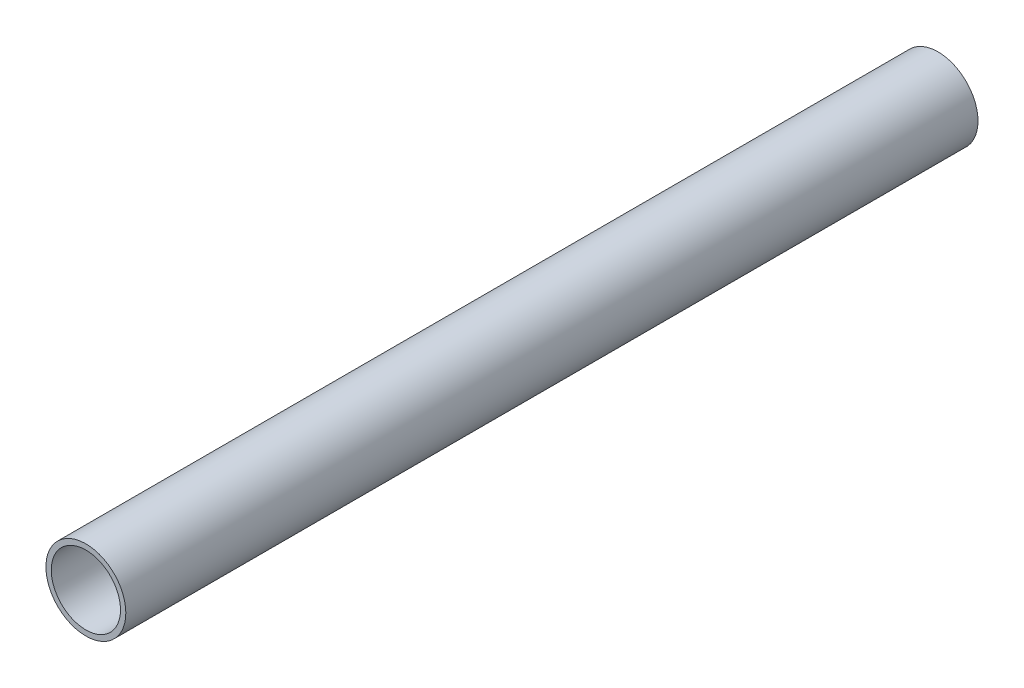
SolidWorks part; units mm, degrees
material "Hexcel AS4C (3000 Filaments)"
ref_plane "Front Plane" through (0, 0, 0) normal (0, 0, 1) x (1, 0, 0)
ref_plane "Top Plane" through (0, 0, 0) normal (0, 1, 0) x (1, 0, 0)
ref_plane "Right Plane" through (0, 0, 0) normal (1, 0, 0) x (0, 0, -1)
sketch "Sketch1" plane through (0, 0, 0) normal (0, 0, 1) x (1, 0, 0)
  circle A0 centre (0, 0) radius 7.5
  circle A1 centre (0, 0) radius 6.5
  dimension "D1" = 15
  dimension "D2" = 13
extrude "Boss-Extrude1" add sketch "Sketch1" along normal blind 160
